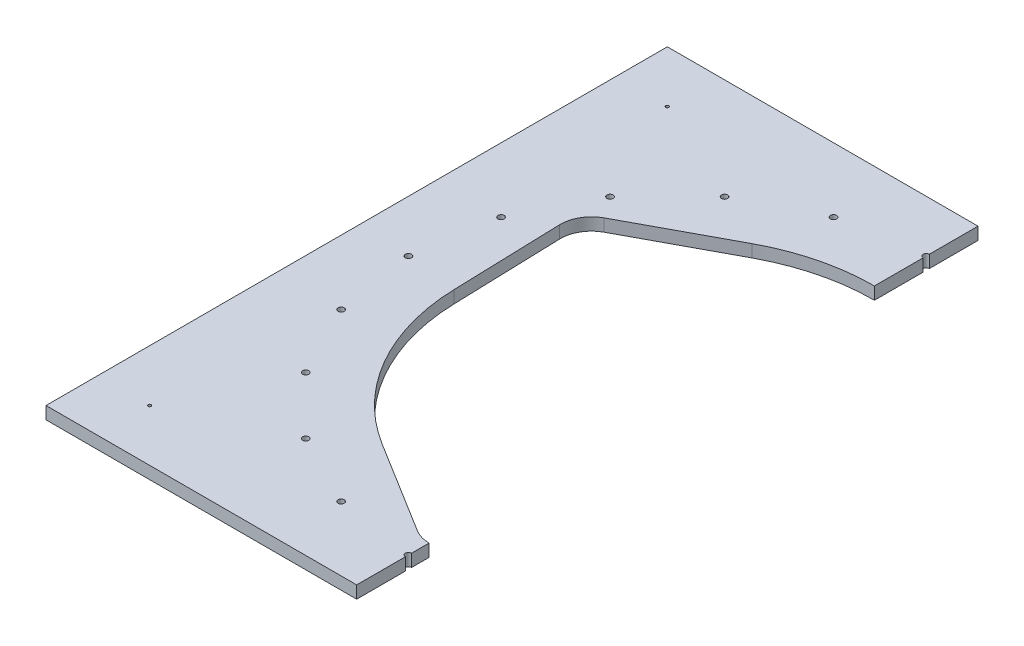
SolidWorks part; units mm, degrees
ref_plane "Front Plane" through (0, 0, 0) normal (0, 0, 1) x (1, 0, 0)
ref_plane "Top Plane" through (0, 0, 0) normal (0, 1, 0) x (1, 0, 0)
ref_plane "Right Plane" through (0, 0, 0) normal (1, 0, 0) x (0, 0, -1)
sketch "Sketch1" plane through (0, 0, 0) normal (0, 1, 0) x (1, 0, 0)
  line L0 (-203.1905, 99.0638) -> (-199.9026, -6.2414)
  line L2 (-300, 300) -> (-300, -300)
  line L5 (-187.387, 126.4362) -> (-94.546, 176.2414)
  line L7 (-15.8035, -225.5) -> (-105.3565, -170)
  line L9 (200.0975, 0) -> (199.9026, -6.2414)
  line L10 (0, 300) -> (0, 253)
  line L11 (-517.8117, 0) -> (247, 0) construction
  line L12 (253, 0) -> (536.3525, 0) construction
  line L13 (0, -253) -> (0, -300)
  line L14 (0, 247) -> (0, 200)
  line L15 (-300, 300) -> (0, 300)
  line L16 (0, -230) -> (0, -247)
  line L17 (-300, -300) -> (0, -300)
  arc A1 (-15.8035, -225.5) -> (0, -230) centre (0, -200) ccw
  arc A2 (-187.387, 126.4362) -> (-203.1905, 99.0638) centre (-173.2051, 100) ccw
  arc A4 (-199.9026, -6.2414) -> (-105.3565, -170) centre (0, 0) ccw
  arc A5 (0, 200) -> (-94.546, 176.2414) centre (0, 0) ccw
  arc A6 (0, 253) -> (0, 247) centre (0, 250) ccw
  arc A16 (0, -247) -> (0, -253) centre (0, -250) ccw
  circle A17 centre (-77.2542, -237.7641) radius 3
  circle A18 centre (-146.9463, -202.2542) radius 3
  circle A19 centre (-202.2542, -146.9463) radius 3
  circle A20 centre (-237.7641, -77.2542) radius 3
  circle A21 centre (-250, 0) radius 3
  circle A22 centre (-237.7641, 77.2542) radius 3
  circle A23 centre (-202.2542, 146.9463) radius 3
  circle A24 centre (-146.9463, 202.2542) radius 3
  circle A25 centre (-77.2542, 237.7641) radius 3
  circle A26 centre (0, 50) radius 3 construction
  circle A27 centre (43.3013, 25) radius 3 construction
  circle A28 centre (43.3013, -25) radius 3 construction
  circle A29 centre (0, -50) radius 3 construction
  circle A30 centre (-43.3013, -25) radius 3 construction
  circle A31 centre (-43.3013, 25) radius 3 construction
  circle A32 centre (-250, 250) radius 1.5
  circle A35 centre (-250, -250) radius 1.5
  arc A36 (203.1905, 99.0638) -> (187.387, 126.4362) centre (173.2051, 100) ccw [skipped]
  circle A37 centre (77.2542, -237.7641) radius 3 [skipped]
  circle A38 centre (146.9463, -202.2542) radius 3 [skipped]
  circle A39 centre (202.2542, -146.9463) radius 3 [skipped]
  circle A40 centre (237.7641, -77.2542) radius 3 [skipped]
  arc A41 (253, 0) -> (247, 0) centre (250, 0) ccw [skipped]
  circle A42 centre (237.7641, 77.2542) radius 3 [skipped]
  circle A43 centre (202.2542, 146.9463) radius 3 [skipped]
  circle A44 centre (146.9463, 202.2542) radius 3 [skipped]
  circle A45 centre (77.2542, 237.7641) radius 3 [skipped]
  point P7 (-300, 0)
  point P26 (0, 0)
  point P67 (0, 0)
  point P79 (0, 0)
  dimension "D4" = 60
  dimension "D6" = 250
  dimension "D7" = 6
  dimension "D10" = 6
  dimension "D12" = 3
  dimension "D1" = 600
  dimension "D9" = 50
  dimension "D13" = 50
  dimension "D5" = 3
  dimension "D8" = 20
  dimension "D11" = 6
extrude "Boss-Extrude1" add sketch "Sketch1" along normal blind 12
